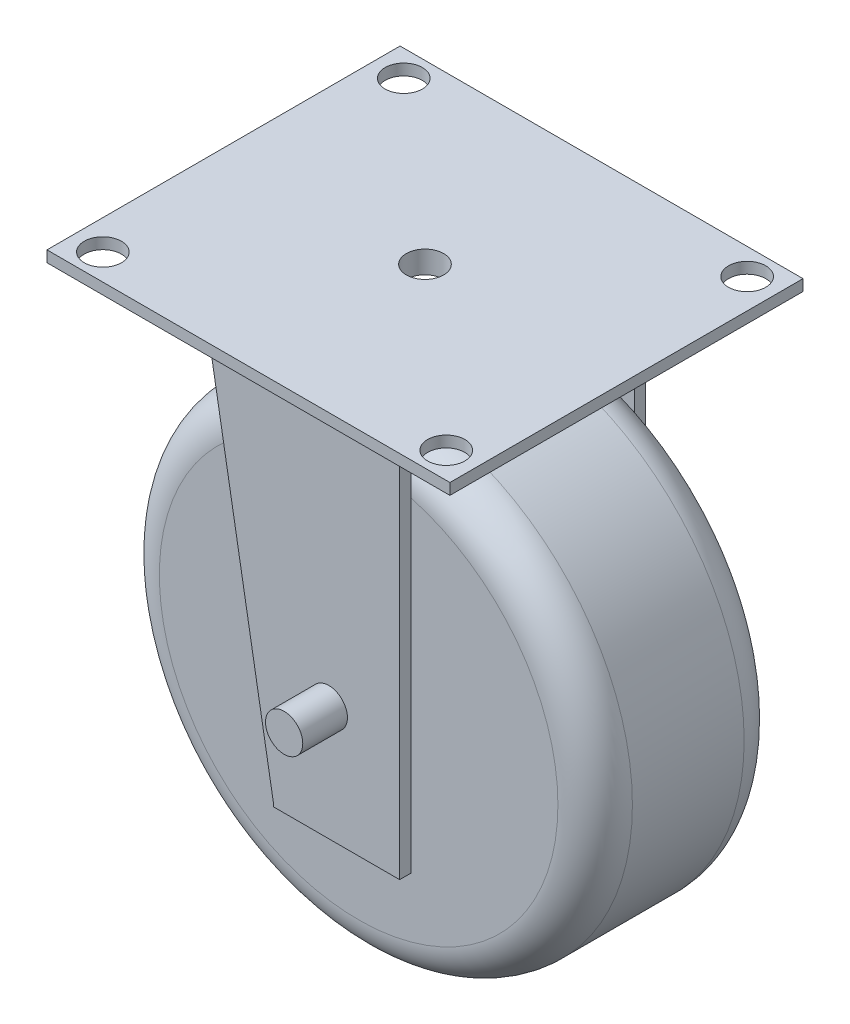
SolidWorks part; units mm, degrees
ref_plane "前视基准面" through (0, 0, 0) normal (0, 0, 1) x (1, 0, 0)
ref_plane "上视基准面" through (0, 0, 0) normal (0, 1, 0) x (1, 0, 0)
ref_plane "右视基准面" through (0, 0, 0) normal (1, 0, 0) x (0, 0, -1)
other "Configuration Table"
sketch "草图1" plane through (0, 0, 0) normal (0, 0, 1) x (1, 0, 0)
  circle A0 centre (0, 0) radius 63.5
extrude "凸台-拉伸1" add sketch "草图1" along normal blind 50
fillet "圆角1" radius 10 2 edges at (63.5, 0, 0) (63.5, 0, 50)
sketch "草图2" plane through (0, 0, 0) normal (0, 0, -1) x (-1, 0, 0)
  circle A0 centre (0, 0) radius 5
extrude "凸台-拉伸2" add sketch "草图2" along normal blind 20
sketch "草图3" plane through (0, 0, 50) normal (0, 0, 1) x (1, 0, 0)
  circle A0 centre (0, 0) radius 5
extrude "凸台-拉伸3" add sketch "草图3" along normal blind 20
ref_plane "基准面1" through (0, 0, 55) normal (0, 0, 1) x (1, 0, 0)
sketch "草图4" plane through (0, 0, 55) normal (0, 0, 1) x (1, 0, 0)
  line L0 (-14.8477, -30.6411) -> (19.0089, -30.6411)
  line L1 (19.0089, -30.6411) -> (19.0089, 76.8505)
  line L2 (19.0089, 76.8505) -> (-33.3757, 76.8505)
  line L3 (-33.3757, 76.8505) -> (-14.8477, -29.8966)
  line L4 (-14.8477, -29.8966) -> (-14.8477, -30.6411)
  circle A0 centre (0, 0) radius 5
extrude "凸台-拉伸4" add sketch "草图4" along normal blind 3
pattern_linear "阵列(线性)1" count 2 spacing 63 along (0, 0, -1) of "凸台-拉伸4"
sketch "草图5" plane through (0, 76.8505, 0) normal (0, 1, 0) x (1, 0, 0)
  line L1 (-33.3757, 8) -> (19.0089, 8)
  line L2 (-33.3757, 8) -> (-33.3757, -58)
  line L3 (-33.3757, -58) -> (19.0089, -58)
  line L4 (19.0089, 8) -> (19.0089, -58)
extrude "凸台-拉伸5" add sketch "草图5" along normal blind 3
sketch "草图6" plane through (0, 79.8505, 0) normal (0, 1, 0) x (1, 0, 0)
  line L0 (-33.3757, 8) -> (19.0089, -58) construction
  line L1 (19.0089, 8) -> (-33.3757, -58) construction
  circle A0 centre (-7.1834, -25) radius 5
extrude "切除-拉伸1" cut sketch "草图6" against normal blind 3
sketch "草图7" plane through (0, 79.8505, 0) normal (0, 1, 0) x (1, 0, 0)
  line L1 (-61.2732, 22.3979) -> (46.9064, 22.3979)
  line L2 (-61.2732, 22.3979) -> (-61.2732, -72.3979)
  line L3 (-61.2732, -72.3979) -> (46.9064, -72.3979)
  line L4 (46.9064, 22.3979) -> (46.9064, -72.3979)
  line L5 (-61.2732, 22.3979) -> (46.9064, -72.3979) construction
  line L6 (-61.2732, -72.3979) -> (46.9064, 22.3979) construction
  line L7 (-53.2775, 15.3914) -> (38.9107, 15.3914)
  line L8 (-53.2775, 15.3914) -> (-53.2775, -65.3914)
  line L9 (-53.2775, -65.3914) -> (38.9107, -65.3914)
  line L10 (38.9107, 15.3914) -> (38.9107, -65.3914)
  line L11 (-53.2775, 15.3914) -> (38.9107, -65.3914) construction
  line L12 (-53.2775, -65.3914) -> (38.9107, 15.3914) construction
  circle A1 centre (-53.2775, 15.3914) radius 5
  circle A2 centre (-53.2775, -65.3914) radius 5
  circle A3 centre (38.9107, -65.3914) radius 5
  circle A4 centre (38.9107, 15.3914) radius 5
  point P0 (-7.1834, -25)
  point P8 (-7.1834, -25)
  circle M13 centre (-7.1834, -25) radius 5
  line M14 (-33.3757, 8) -> (-33.3757, -58)
  line M15 (-33.3757, -58) -> (19.0089, -58)
  line M16 (19.0089, -58) -> (19.0089, 8)
  line M17 (19.0089, 8) -> (-33.3757, 8)
extrude "凸台-拉伸6" add sketch "草图7" along normal blind 3 contours L4 L1 L2 L3 A4 L10 A3 L9 A2 L8 A1 L7 | A4 L7 A1 L8 A2 L9 A3 L10 M14 M17 M16 M15 | M17 M14 M15 M16 M13
